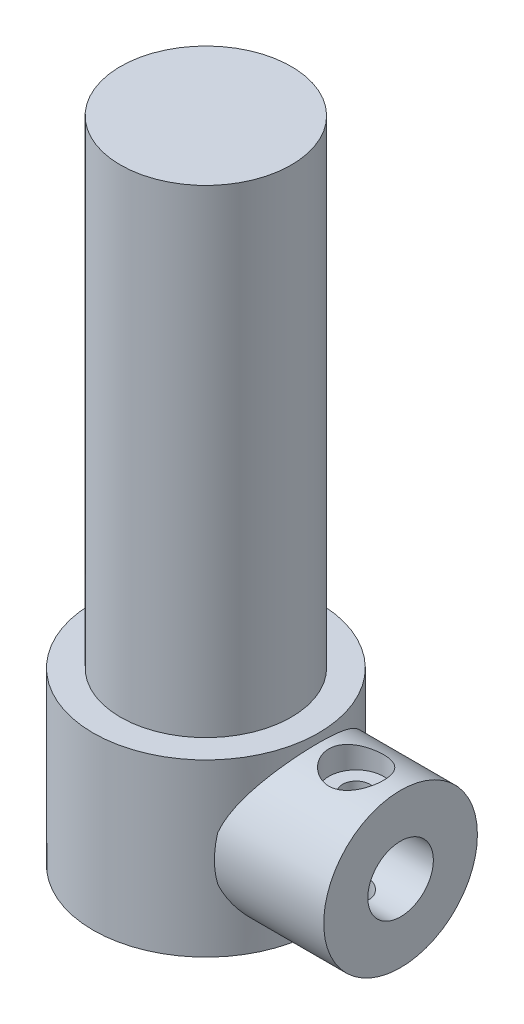
SolidWorks part; units mm, degrees
ref_plane "Plan de face" through (0, 0, 0) normal (0, 0, 1) x (1, 0, 0)
ref_plane "Plan de dessus" through (0, 0, 0) normal (0, 1, 0) x (1, 0, 0)
ref_plane "Plan de droite" through (0, 0, 0) normal (1, 0, 0) x (0, 0, -1)
sketch "Esquisse1" plane through (0, 0, 0) normal (0, 1, 0) x (1, 0, 0)
  circle A0 centre (0, 0) radius 16.5
  dimension "D1" = 33
extrude "Boss.-Extru.1" add sketch "Esquisse1" along normal blind 25
sketch "Esquisse2" plane through (0, 0, 0) normal (0, -1, 0) x (1, 0, 0)
  circle A0 centre (0, 0) radius 4.75
  dimension "D1" = 9.5
ref_plane "Plan1" through (16.5, 0, 0) normal (1, 0, 0) x (0, 0, -1)
sketch "Esquisse9" plane through (16.5, 0, 0) normal (1, 0, 0) x (0, 0, -1)
  line L0 (0, 24.75) -> (0, -24.75) construction
  line L1 (16.5, 25) -> (-16.5, 25) construction
  circle A0 centre (0, 12.5) radius 11.25
  dimension "D1" = 22.5
  dimension "D3" = 12.5
extrude "Boss.-Extru.4" add sketch "Esquisse9" along normal blind 12 and the other way blind 4
sketch "Esquisse10" plane through (28.5, 0, 0) normal (1, 0, 0) x (0, 0, -1)
  line L0 (0, 24.75) -> (0, -24.75) construction
  circle A0 centre (0, 12.5) radius 4.8
  circle A2 centre (0, 12.5) radius 11.25 construction
  dimension "D1" = 9.6
extrude "Enlèv. mat.-Extru.3" cut sketch "Esquisse10" against normal blind 13
ref_plane "Plan2" through (0, 1.25, 0) normal (0, 1, 0) x (1, 0, 0)
ref_plane "Plan3" through (0, 23.75, 0) normal (0, 1, 0) x (1, 0, 0)
ref_plane "Plan4" through (0, 12.5, 0) normal (0, 1, 0) x (1, 0, 0)
sketch "Esquisse11" plane through (0, 1.25, 0) normal (0, 1, 0) x (1, 0, 0)
  line L0 (-24.75, 0) -> (24.75, 0) construction
  line L1 (28.5, -11.25) -> (28.5, 11.25) construction
  circle A0 centre (22, 0) radius 4
  dimension "D1" = 8
  dimension "D2" = 6.5
extrude "Enlèv. mat.-Extru.4" cut sketch "Esquisse11" along normal blind 3.5
sketch "Esquisse12" plane through (0, 4.75, 0) normal (0, -1, 0) x (1, 0, 0)
  circle A0 centre (22, 0) radius 2
  circle A1 centre (22, 0) radius 4 construction
  dimension "4" = 4
extrude "Enlèv. mat.-Extru.5" cut sketch "Esquisse12" against normal up to next
mirror "Symétrie1" about plane through (0, 0, 0) normal (0, 0, 1) of "Enlèv. mat.-Extru.4", "Enlèv. mat.-Extru.5"
sketch "Esquisse13" plane through (0, 25, 0) normal (0, 1, 0) x (1, 0, 0)
  circle A0 centre (0, 0) radius 12.5
  dimension "D1" = 25
extrude "Boss.-Extru.5" add sketch "Esquisse13" along normal blind 70
sketch "Esquisse15" plane through (0, 0, 0) normal (0, -1, 0) x (1, 0, 0)
  circle A0 centre (0, 0) radius 8
  dimension "D1" = 16
extrude "Boss.-Extru.6" add sketch "Esquisse15" along normal blind 1.2
extrude "Enlèv. mat.-Extru.6" cut sketch "Esquisse2" against normal blind 40 and the other way up to next contours A0
